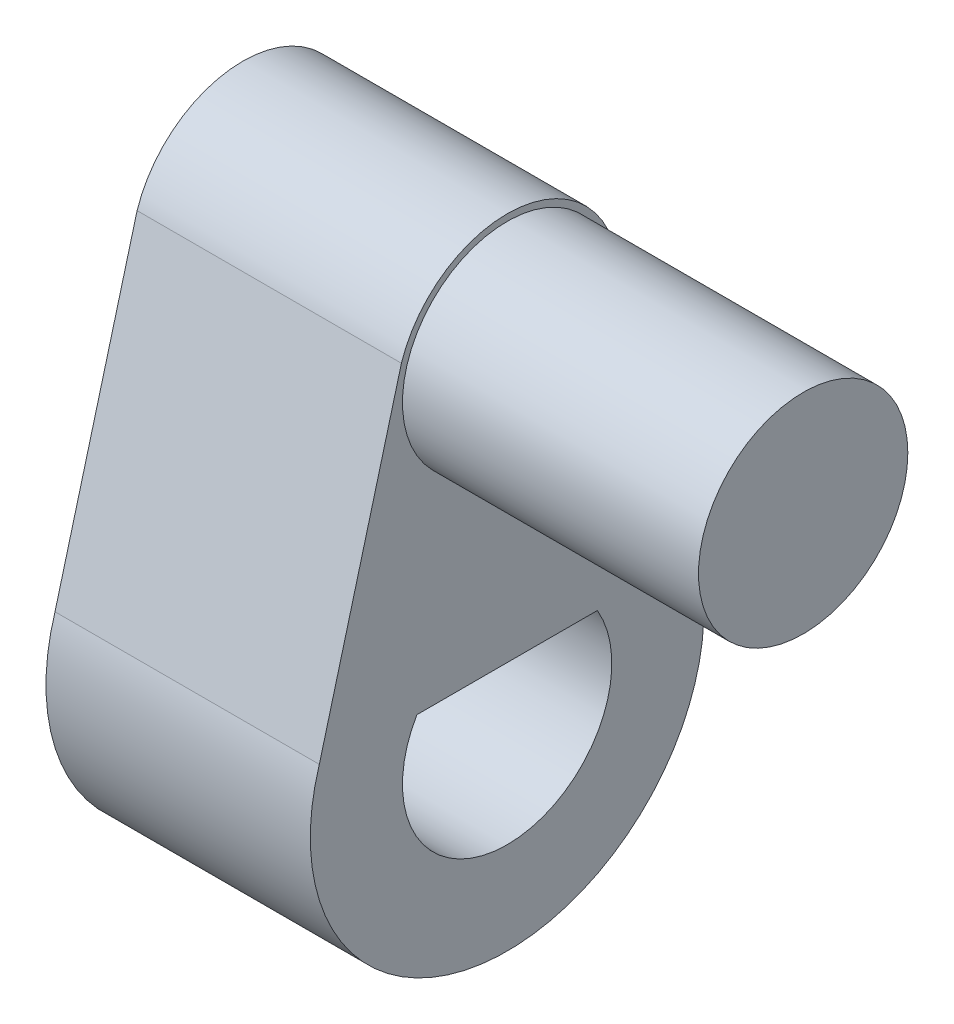
SolidWorks part; units mm, degrees
ref_plane "Front Plane" through (0, 0, 0) normal (0, 0, 1) x (1, 0, 0)
ref_plane "Top Plane" through (0, 0, 0) normal (0, 1, 0) x (1, 0, 0)
ref_plane "Right Plane" through (0, 0, 0) normal (1, 0, 0) x (0, 0, -1)
sketch "Sketch3" plane through (0, 0, 0) normal (1, 0, 0) x (0, 0, -1)
  line L2 (-54.6708, 30.9688) -> (-55.4472, 28.071)
  line L3 (-52.6708, 30.9688) -> (-51.8943, 28.071)
  arc A0 (-52.6708, 30.9688) -> (-54.6708, 30.9688) centre (-53.6708, 30.6404) ccw
  arc A1 (-55.4472, 28.071) -> (-51.8943, 28.071) centre (-53.6708, 27.5142) ccw
  dimension "D3" = 3
  dimension "D4" = 3
  dimension "D5" = 0
extrude "Boss-Extrude2" add sketch "Sketch3" along normal blind 2.5
sketch "Sketch4" plane through (2.5, 0, 0) normal (1, 0, 0) x (0, 0, -1)
  circle A0 centre (-53.6708, 27.5142) radius 0.99
  dimension "D1" = 1.98
extrude "Cut-Extrude2" cut sketch "Sketch4" against normal through all
sketch "Sketch6" plane through (2.5, 0, 0) normal (1, 0, 0) x (0, 0, -1)
  circle A0 centre (-53.6708, 30.6404) radius 0.99
  dimension "D1" = 1.98
extrude "Boss-Extrude4" add sketch "Sketch6" along normal blind 2.8
sketch "Sketch7" plane through (2.5, 0, 0) normal (1, 0, 0) x (0, 0, -1)
  line L1 (-54.6674, 28.0164) -> (-52.6476, 28.0164)
  line L2 (-54.6674, 28.0164) -> (-54.6674, 28.8013)
  line L3 (-54.6674, 28.8013) -> (-52.6476, 28.8013)
  line L4 (-52.6476, 28.0164) -> (-52.6476, 28.8013)
extrude "Boss-Extrude5" add sketch "Sketch7" against normal up to surface (2.5 mm away) up to face at (0, 27.5142, 52.6808)
